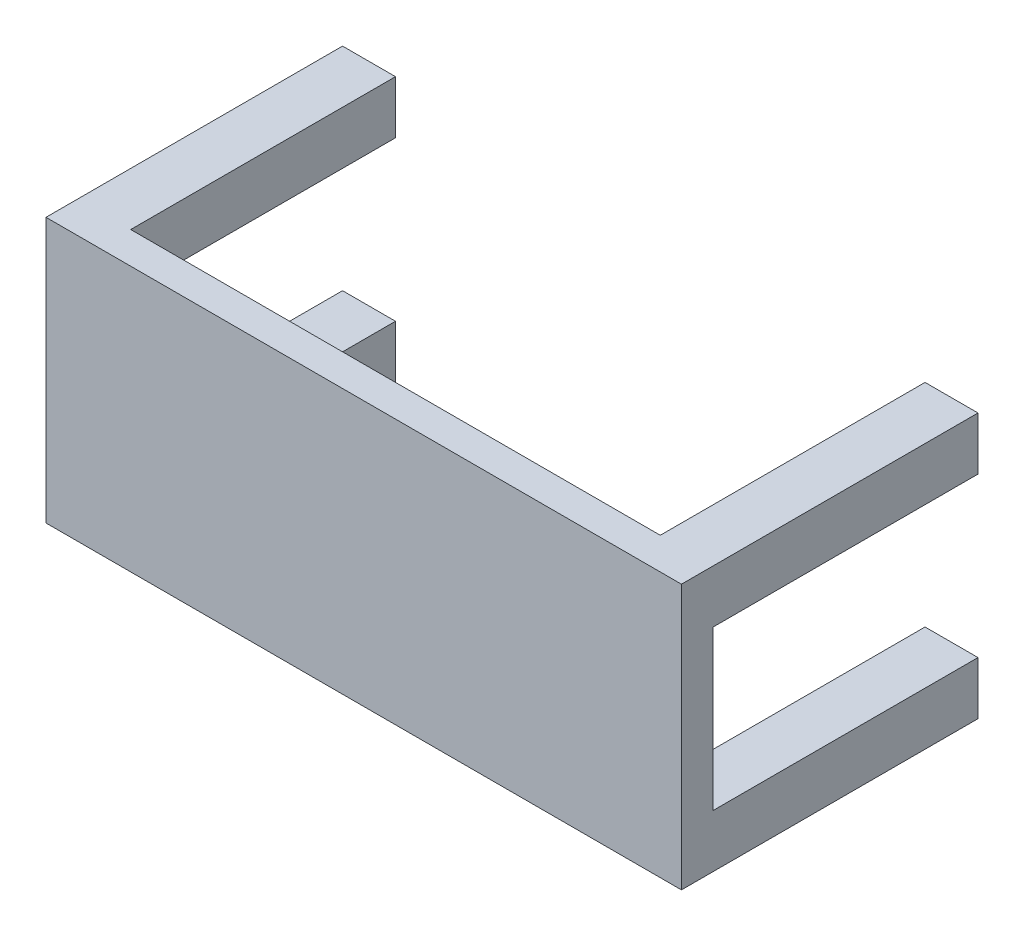
SolidWorks part; units mm, degrees
material "Plastique personnalisé"
ref_plane "Plan de face" through (0, 0, 0) normal (0, 0, 1) x (1, 0, 0)
ref_plane "Plan de dessus" through (0, 0, 0) normal (0, 1, 0) x (1, 0, 0)
ref_plane "Plan de droite" through (0, 0, 0) normal (1, 0, 0) x (0, 0, -1)
sketch "Esquisse1" plane through (0, 0, 0) normal (0, 1, 0) x (1, 0, 0)
  line L0 (36.8649, -13.8851) -> (36.8649, 11.1149)
  line L1 (-18.1351, 11.1149) -> (-13.1351, 11.1149)
  line L2 (-18.1351, 11.1149) -> (-18.1351, -16.8851)
  line L3 (-18.1351, -16.8851) -> (-13.1351, -16.8851)
  line L4 (-13.1351, 11.1149) -> (-13.1351, -13.8851)
  line L5 (-13.1351, -16.8851) -> (36.8649, -16.8851)
  line L7 (-13.1351, -13.8851) -> (36.8649, -13.8851)
  line L9 (36.8649, -16.8851) -> (41.8649, -16.8851)
  line L11 (36.8649, 11.1149) -> (41.8649, 11.1149)
  line L12 (41.8649, -16.8851) -> (41.8649, 11.1149)
  dimension "D1" = 5
  dimension "D2" = 3
  dimension "D3" = 5
  dimension "D4" = 25
  dimension "D5" = 25
  dimension "D6" = 50
extrude "Boss.-Extru.1" add sketch "Esquisse1" along normal blind 25 contours L4 L7 L0 L11 L12 L9 L5 L3 L2 L1
ref_plane "Plan1" through (41.8649, 0, 0) normal (1, 0, 0) x (0, 0, -1)
sketch "Esquisse2" plane through (41.8649, 0, 0) normal (1, 0, 0) x (0, 0, -1)
  line L0 (11.1149, 25) -> (11.1149, 0) construction
  line L1 (11.1149, 20) -> (-13.8851, 20)
  line L2 (11.1149, 20) -> (11.1149, 5)
  line L3 (11.1149, 5) -> (-13.8851, 5)
  line L4 (-13.8851, 20) -> (-13.8851, 5)
  line L5 (-16.8851, 25) -> (-16.8851, 0) construction
  line L6 (-16.8851, 25) -> (11.1149, 25) construction
  line L7 (-16.8851, 0) -> (11.1149, 0) construction
  dimension "D1" = 3
  dimension "D2" = 5
  dimension "D3" = 5
extrude "Enlèv. mat.-Extru.1" cut sketch "Esquisse2" against normal blind 106
